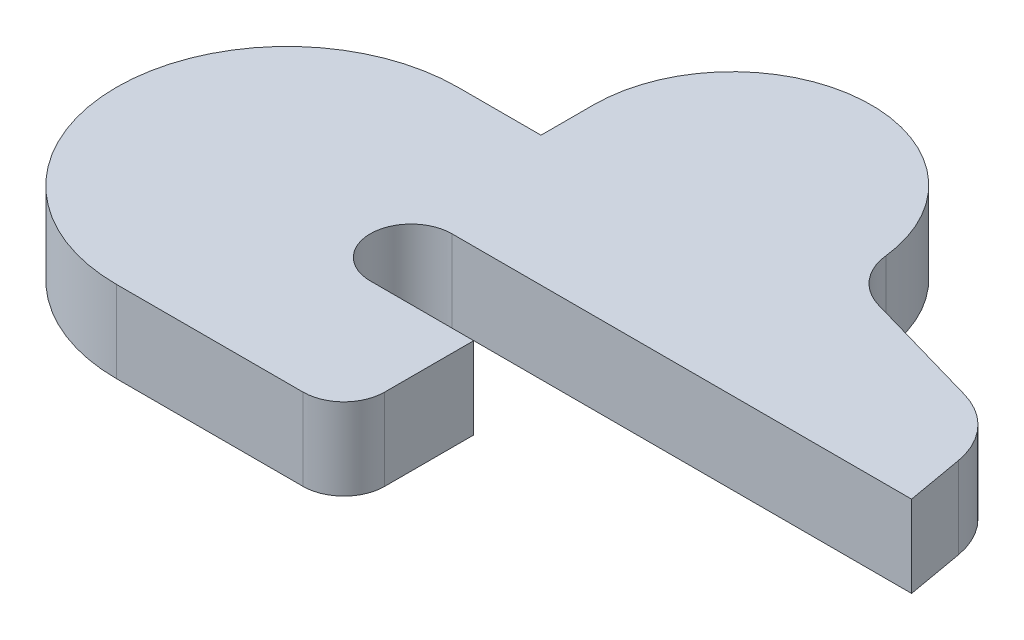
SolidWorks part; units mm, degrees
ref_plane "Front Plane" through (0, 0, 0) normal (0, 0, 1) x (1, 0, 0)
ref_plane "Top Plane" through (0, 0, 0) normal (0, 1, 0) x (1, 0, 0)
ref_plane "Right Plane" through (0, 0, 0) normal (1, 0, 0) x (0, 0, -1)
sketch "Sketch1" plane through (0, 0, 0) normal (0, 1, 0) x (1, 0, 0)
  line L0 (0, 0) -> (-3.8, 0)
  line L1 (-3.8, 3) -> (13.0795, 3)
  line L2 (13.0795, 3) -> (12.7106, 5.092)
  line L6 (-5.3, 9.6979) -> (-5.3, 7.77)
  line L7 (-5.3, 7.77) -> (-8.3505, 7.77)
  line L9 (0, -3.27) -> (0, 0)
  line L10 (-8.3505, -4.77) -> (-1.5, -4.77)
  line L11 (6.3047, 8.5648) -> (10.725, 7.2973)
  arc A0 (-3.8, 0) -> (-3.8, 3) centre (-3.8, 1.5) cw
  arc A5 (-8.3505, 7.77) -> (-8.3505, -4.77) centre (-8.3505, 1.5) ccw
  arc A10 (-1.5, -4.77) -> (0, -3.27) centre (-1.5, -3.27) ccw
  arc A11 (-5.3, 9.6979) -> (4.8684, 10.2649) centre (-0.2, 9.6979) cw
  arc A12 (4.8684, 10.2649) -> (6.3047, 8.5648) centre (6.856, 10.4873) ccw
  arc A13 (12.7106, 5.092) -> (10.725, 7.2973) centre (9.9532, 4.6058) ccw
  point P6 (0, 0)
  point P10 (-0.484, 14.79)
  point P12 (-14.6205, 1.5)
  point P15 (4.8495, 8.982)
  point P17 (0, 0)
  point P19 (0, 0)
  point P26 (-3.8, 0)
  point P27 (0, 0)
  point P29 (-3.8, 0)
  point P30 (-3.8, 2.759)
  point P31 (0, 0)
  point P32 (-3.8, 3.4815)
  point P33 (0, 0)
  point P34 (0, 0)
  point P44 (-5.3, 1.5)
  dimension "10.9" = 6.27
  dimension "D4" = 16.8795
  dimension "D5" = 19.56
  dimension "D6" = 16
  dimension "D7" = 2
  dimension "D11" = 1.5
  dimension "D2" = 5.1
  dimension "D3" = 2.8
  dimension "1.5" = 1.5
  dimension "80" = 80
  dimension "D9" = 3.8
  dimension "5" = 8.23
  dimension "27.7" = 27.7
extrude "Boss-Extrude2" add sketch "Sketch1" along normal blind 3
